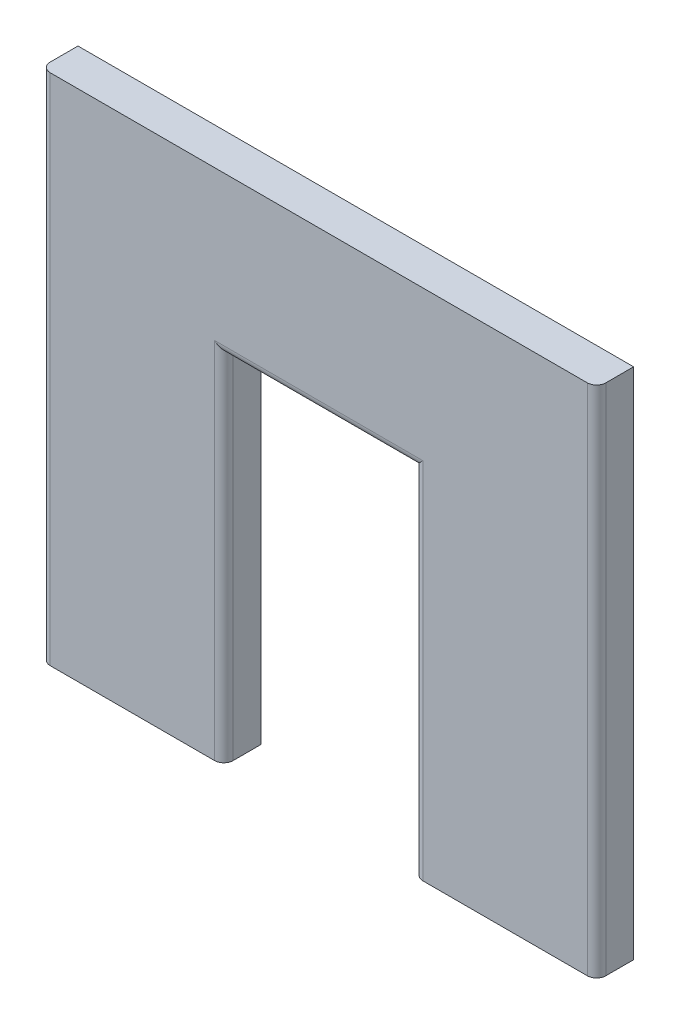
SolidWorks part; units mm, degrees
ref_plane "Front Plane" through (0, 0, 0) normal (0, 0, 1) x (1, 0, 0)
ref_plane "Top Plane" through (0, 0, 0) normal (0, 1, 0) x (1, 0, 0)
ref_plane "Right Plane" through (0, 0, 0) normal (1, 0, 0) x (0, 0, -1)
sketch "Sketch1" plane through (0, 0, 0) normal (0, 0, 1) x (1, 0, 0)
  line L1 (-15, -13.8636) -> (15, -13.8636)
  line L2 (-15, -13.8636) -> (-15, 13.8636)
  line L3 (-15, 13.8636) -> (15, 13.8636)
  line L4 (15, -13.8636) -> (15, 13.8636)
  line L5 (-15, -13.8636) -> (15, 13.8636) construction
  line L6 (-15, 13.8636) -> (15, -13.8636) construction
  point P0 (0, 0)
  dimension "D1" = 30
extrude "Boss-Extrude1" add sketch "Sketch1" along normal blind 2
sketch "Sketch2" plane through (0, 0, 2) normal (0, 0, 1) x (1, 0, 0)
  line L1 (5.1244, -13.8723) -> (-5.1244, -13.8723)
  line L2 (5.1244, -13.8723) -> (5.1244, 5.2837)
  line L3 (5.1244, 5.2837) -> (-5.1244, 5.2837)
  line L4 (-5.1244, -13.8723) -> (-5.1244, 5.2837)
  point P0 (0, 0)
  point P5 (0, 5.2837)
extrude "Cut-Extrude1" cut sketch "Sketch2" against normal blind 2
fillet "Fillet1" radius 0.5 1 edges at (-15, 0, 2)
fillet "Fillet2" radius 0.5 1 edges at (15, 0, 2)
fillet "Fillet3" radius 0.5 1 edges at (-5.1244, -4.2899, 2)
fillet "Fillet4" radius 0.5 1 edges at (5.1244, -4.2899, 2)
fillet "Fillet5" radius 0.5 1 edges at (0, 5.2837, 2)
